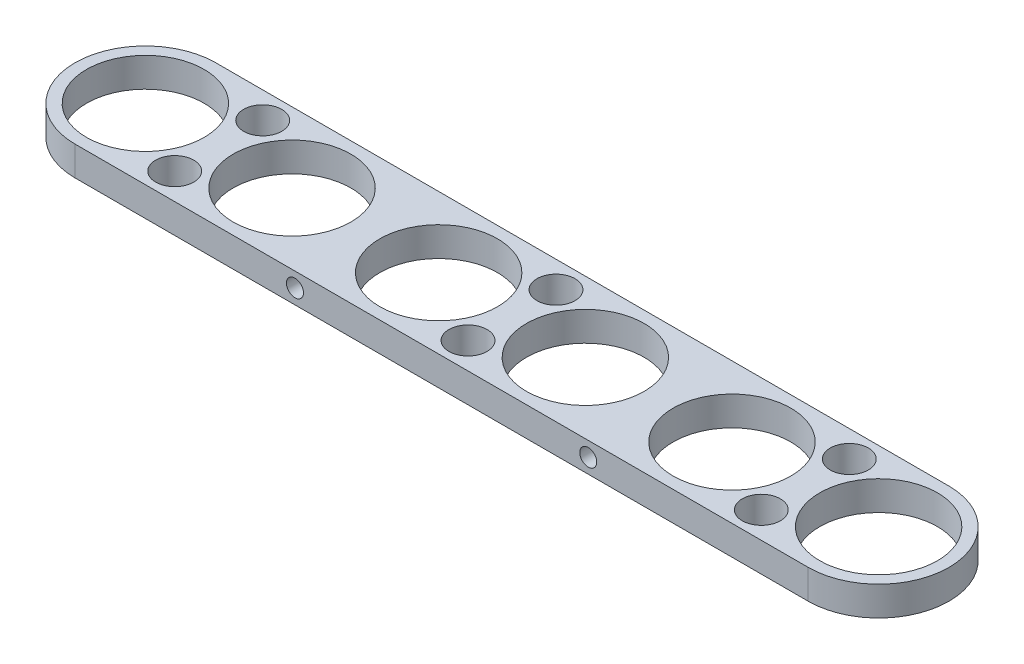
SolidWorks part; units mm, degrees
ref_plane "Front Plane" through (0, 0, 0) normal (0, 0, 1) x (1, 0, 0)
ref_plane "Top Plane" through (0, 0, 0) normal (0, 1, 0) x (1, 0, 0)
ref_plane "Right Plane" through (0, 0, 0) normal (1, 0, 0) x (0, 0, -1)
sketch "Sketch1" plane through (0, 0, 0) normal (0, 1, 0) x (1, 0, 0)
  line L0 (15.875, 0) -> (15.875, 15.24) construction
  line L1 (-15.24, 0) -> (31.75, 0) construction
  line L3 (0, -15.24) -> (158.75, -15.24)
  line L4 (0, 15.24) -> (158.75, 15.24)
  circle A0 centre (0, 0) radius 12.7441
  circle A1 centre (31.75, 0) radius 12.7441
  circle A2 centre (63.5, 0) radius 12.7441
  circle A3 centre (95.25, 0) radius 12.7441
  circle A4 centre (127, 0) radius 12.7441
  circle A5 centre (158.75, 0) radius 12.7441
  arc A6 (0, 15.24) -> (0, -15.24) centre (0, 0) ccw
  arc A7 (158.75, -15.24) -> (158.75, 15.24) centre (158.75, 0) ccw
  circle A8 centre (15.875, -9.525) radius 4.1275
  circle A9 centre (15.875, 9.525) radius 4.1275
  circle A10 centre (79.375, 9.525) radius 4.1275
  circle A11 centre (79.375, -9.525) radius 4.1275
  circle A12 centre (142.875, 9.525) radius 4.1275
  circle A13 centre (142.875, -9.525) radius 4.1275
  point P15 (77.8124, 0)
  dimension "D1" = 15.875
  dimension "D3" = 15.24
  dimension "D5" = 25.4882
  dimension "D6" = 5.715
  dimension "D7" = 8.255
  dimension "D2" = 31.75
  dimension "D4" = 6
extrude "Boss-Extrude1" add sketch "Sketch1" along normal blind 6.35
sketch "Sketch2" plane through (0, 0, -15.24) normal (0, 0, -1) x (-1, 0, 0)
  line L0 (-158.75, 6.35) -> (-158.75, 0) construction
  line L1 (-158.75, 0) -> (0, 0) construction
  line L2 (-79.375, 6.35) -> (-79.375, 0) construction
  line L3 (-158.75, 6.35) -> (0, 6.35) construction
  circle A0 centre (-111.125, 3.175) radius 1.8415
  circle A1 centre (-47.625, 3.175) radius 1.8415
  point P2 (-158.75, 3.175)
  dimension "D2" = 3.175
  dimension "D3" = 3.683
  dimension "D1" = 47.625
extrude "Cut-Extrude1" cut sketch "Sketch2" against normal through all
